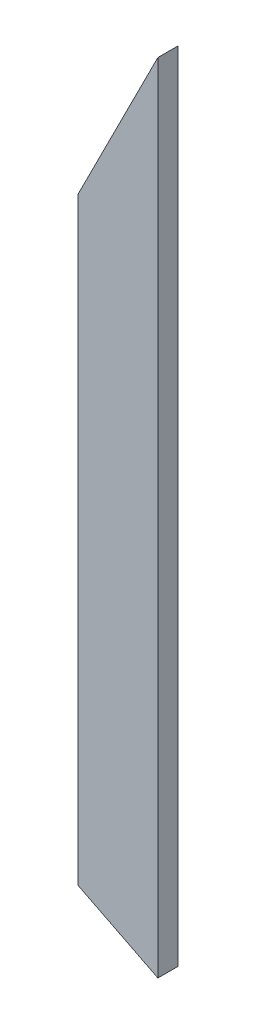
SolidWorks part; units mm, degrees
ref_plane "Front Plane" through (0, 0, 0) normal (0, 0, 1) x (1, 0, 0)
ref_plane "Top Plane" through (0, 0, 0) normal (0, 1, 0) x (1, 0, 0)
ref_plane "Right Plane" through (0, 0, 0) normal (1, 0, 0) x (0, 0, -1)
sketch "Sketch1" plane through (0, 0, 0) normal (0, 0, 1) x (1, 0, 0)
  line L0 (25.4, 254) -> (-25.4, 153.3134)
  line L1 (-25.4, 254) -> (25.4, 254)
  line L2 (-25.4, 254) -> (-25.4, -254)
  line L3 (-25.4, -254) -> (25.4, -254)
  line L4 (25.4, 254) -> (25.4, -254)
  line L5 (-25.4, 254) -> (25.4, -254) construction
  line L6 (-25.4, -254) -> (25.4, 254) construction
  line L7 (25.4, -254) -> (-25.4, -228.3775)
  point P0 (0, 0)
  dimension "D1" = 508
  dimension "D2" = 50.8
  dimension "D3" = 112.776
  dimension "D4" = 56.896
extrude "Boss-Extrude1" add sketch "Sketch1" along normal blind 12.7
